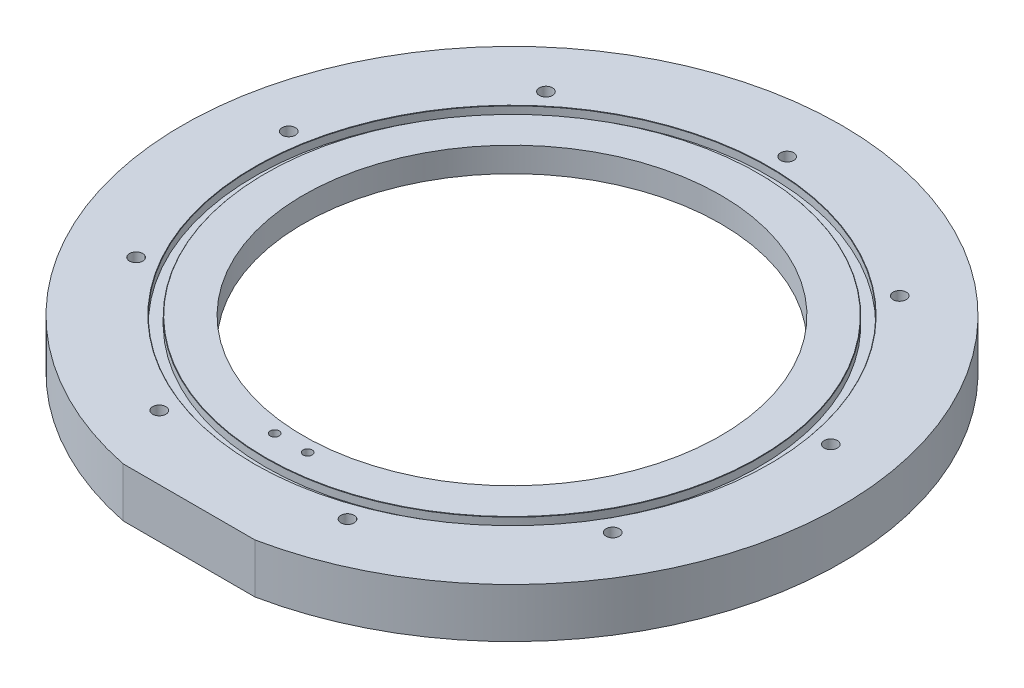
SolidWorks part; units mm, degrees
material "AISI 304"
ref_plane "Front" through (0, 0, 0) normal (0, 0, 1) x (1, 0, 0)
ref_plane "Top" through (0, 0, 0) normal (0, 1, 0) x (1, 0, 0)
ref_plane "Right" through (0, 0, 0) normal (1, 0, 0) x (0, 0, -1)
sketch "Sketch1" plane through (0, 0, 0) normal (0, 0, 1) x (1, 0, 0)
  line L0 (0, 0) -> (0, 19.05) construction
  line L1 (109.7915, 0) -> (109.7915, 2.54)
  line L2 (109.7915, 0) -> (127, 0)
  line L3 (127, 0) -> (127, 19.05)
  line L4 (127, 19.05) -> (105.7783, 19.05)
  line L5 (109.7915, 2.54) -> (105.7783, 2.54)
  line L6 (105.7783, 2.54) -> (105.7783, 19.05) construction
  line L7 (105.7783, 19.05) -> (80.3783, 19.05)
  line L8 (80.3783, 19.05) -> (80.3783, 9.525)
  line L9 (80.3783, 2.54) -> (99.4283, 2.54) construction
  line L10 (80.3783, 9.525) -> (99.4283, 9.525)
  line L11 (99.4283, 9.525) -> (99.4283, 2.54)
  line L12 (99.4283, 2.54) -> (105.7783, 2.54)
  line L13 (80.3783, 9.525) -> (80.3783, 2.54) construction
  dimension "D1" = 219.583
  dimension "D2" = 254
  dimension "D3" = 19.05
  dimension "D4" = 105.7783
  dimension "D5" = 25.4
  dimension "D6" = 2.54
  dimension "D7" = 9.525
  dimension "D8" = 19.05
revolve "Revolve1" add sketch "Sketch1" angle 360 about L0
hole_wizard "1/4-20 Tapped Hole1" positions "Sketch2" profile "Sketch3" tap size "1/4-20" standard "ANSI Inch"
sketch "Sketch2" plane through (0, 19.05, 0) normal (0, 1, 0) x (1, 0, 0)
  line L0 (0, 0) -> (0, 106.045) construction
  point P0 (0, 106.045)
  point P6 (68.1644, 81.2352)
  point P7 (104.4339, 18.4145)
  point P8 (91.8377, -53.0225)
  point P9 (36.2695, -99.6497)
  point P10 (-36.2695, -99.6497)
  point P11 (-91.8377, -53.0225)
  point P12 (-104.4339, 18.4145)
  point P13 (-68.1644, 81.2352)
  dimension "D2" = 106.045
  dimension "D1" = 9
cosmetic thread "Hole Thread1" parameters "D1"=9.525, "D2"=6.35
cosmetic thread "Hole Thread2" parameters "D1"=9.525, "D2"=6.35
cosmetic thread "Hole Thread3" parameters "D1"=9.525, "D2"=6.35
cosmetic thread "Hole Thread4" parameters "D1"=9.525, "D2"=6.35
cosmetic thread "Hole Thread5" parameters "D1"=9.525, "D2"=6.35
cosmetic thread "Hole Thread6" parameters "D1"=9.525, "D2"=6.35
cosmetic thread "Hole Thread7" parameters "D1"=9.525, "D2"=6.35
cosmetic thread "Hole Thread8" parameters "D1"=9.525, "D2"=6.35
cosmetic thread "Hole Thread9" parameters "D1"=9.525, "D2"=6.35
sketch "Sketch3" plane through (0, 19.05, -106.045) normal (1, 0, 0) x (0, 0, 1)
  line L0 (0, 0) -> (0, 14.8688)
  line L1 (0, 14.8688) -> (2.5527, 13.335)
  line L2 (2.5527, 13.335) -> (2.5527, 0)
  line L5 (2.5527, 0) -> (0, 0)
  line L10 (0, 14.8688) -> (-2.5527, 13.335) construction
  line L11 (0, -6.35) -> (0, 107.95) construction
  dimension "Tap Drill Dia." = 5.1054
  dimension "Tap Drill Depth" = 13.335
  dimension "Drill Angle" = 118
sketch "Sketch4" plane through (0, 0, 0) normal (0, 0, 1) x (1, 0, 0)
  line L0 (0, 19.05) -> (0, 0) construction
  line L2 (127, 19.05) -> (-127, 19.05) construction
  line L3 (95.0468, 19.05) -> (99.1108, 19.05)
  line L4 (95.0468, 19.05) -> (95.0468, 15.9766)
  line L5 (95.0468, 15.9766) -> (99.1108, 15.9766)
  line L6 (99.1108, 19.05) -> (99.1108, 15.9766)
  line L7 (80.3783, 19.05) -> (-80.3783, 19.05) construction
  dimension "D1" = 190.0936
  dimension "D2" = 198.2216
  dimension "D3" = 3.0734
  dimension "D4" = 4.064
revolve "Cut-Revolve1" cut sketch "Sketch4" angle 360 about L0
chamfer "Chamfer1" distance 0.127 angle 45 2 edges at (0, 19.05, 95.0468) (0, 19.05, 99.1108)
hole_wizard "#8-32 Tapped Hole1" positions "Sketch5" profile "Sketch6" tap size "#8-32" standard "ANSI Inch" end condition up to next
sketch "Sketch5" plane through (0, 9.525, 0) normal (0, -1, 0) x (-1, 0, 0)
  line L0 (-6.35, -85.09) -> (6.35, -85.09) construction
  line L2 (0, -85.09) -> (0, 0) construction
  point P0 (6.35, -85.09)
  point P2 (-6.35, -85.09)
  dimension "D1" = 12.7
  dimension "D2" = 85.09
cosmetic thread "Hole Thread10" parameters "D2"=4.1656
cosmetic thread "Hole Thread11" parameters "D2"=4.1656
sketch "Sketch6" plane through (-6.35, 9.525, 85.09) normal (1, 0, 0) x (0, 0, -1)
  line L0 (0, 0) -> (0, 9.525)
  line L1 (0, 9.525) -> (1.7272, 9.525)
  line L2 (1.7272, 9.525) -> (1.7272, 0)
  line L5 (1.7272, 0) -> (0, 0)
  line L11 (0, -6.35) -> (0, 107.95) construction
  dimension "Thru Tap Drill Dia." = 3.4544
  dimension "Thru Tap Drill Depth" = 9.525
sketch "Sketch7" plane through (0, 19.05, 0) normal (0, 1, 0) x (1, 0, 0)
  line L1 (-25.4, -124.4341) -> (25.4, -124.4341)
  line L2 (-25.4, -124.4341) -> (-25.4, -127)
  line L3 (-25.4, -127) -> (25.4, -127)
  line L4 (25.4, -124.4341) -> (25.4, -127)
  circle A0 centre (0, 0) radius 127 construction
  dimension "D1" = 50.8
extrude "Cut-Extrude1" cut sketch "Sketch7" against normal up to next
